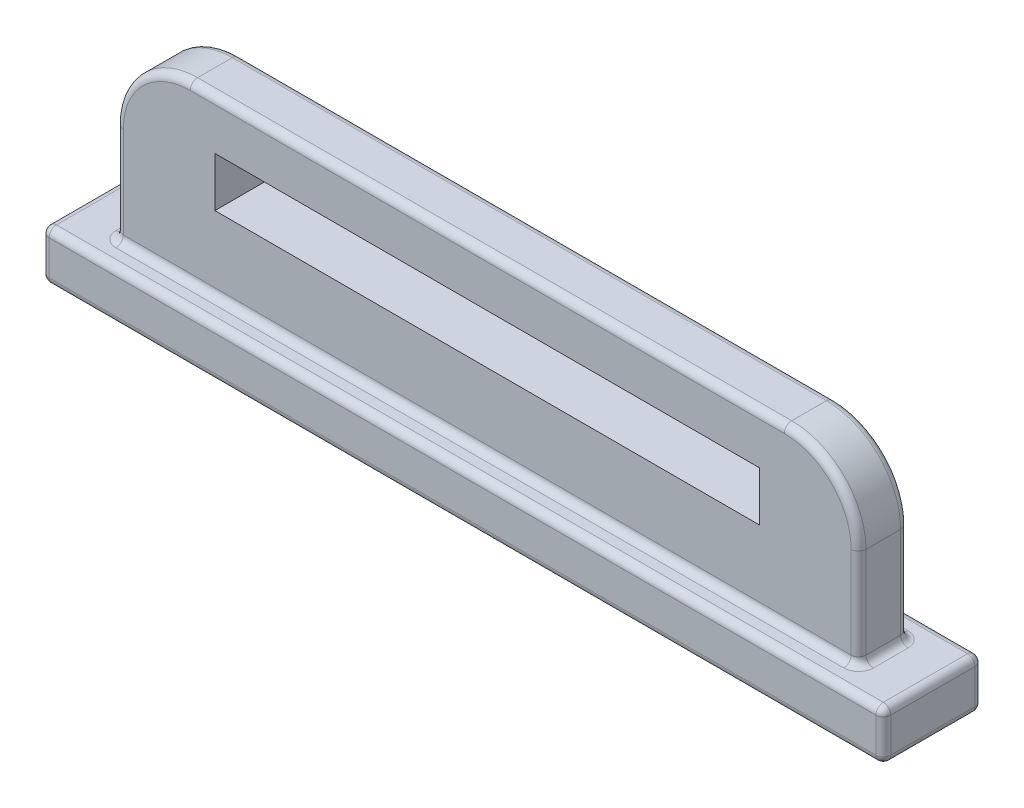
SolidWorks part; units mm, degrees
material "Plain Carbon Steel"
ref_plane "Front Plane" through (0, 0, 0) normal (0, 0, 1) x (1, 0, 0)
ref_plane "Top Plane" through (0, 0, 0) normal (0, 1, 0) x (1, 0, 0)
ref_plane "Right Plane" through (0, 0, 0) normal (1, 0, 0) x (0, 0, -1)
sketch "Sketch1" plane through (0, 0, 0) normal (0, 0, 1) x (1, 0, 0)
  line L0 (-110, 15) -> (-110, -5)
  line L1 (-150, -35) -> (150, -35)
  line L2 (-150, -35) -> (-150, 5)
  line L3 (-120, 35) -> (120, 35)
  line L4 (150, -35) -> (150, 5)
  line L5 (-150, -35) -> (150, 35) construction
  line L6 (-150, 35) -> (150, -35) construction
  line L7 (-110, 15) -> (110, 15)
  line L11 (-110, -5) -> (110, -5)
  line L12 (110, -5) -> (110, 15)
  arc A0 (120, 35) -> (150, 5) centre (120, 5) cw
  arc A1 (-150, 5) -> (-120, 35) centre (-120, 5) cw
  point P0 (0, 0)
  point P6 (0, 7.0518)
  dimension "D6" = 30
  dimension "D1" = 300
  dimension "D2" = 220
  dimension "D3" = 20
  dimension "D4" = 70
  dimension "D5" = 20
extrude "Boss-Extrude1" add sketch "Sketch1" along normal mid plane 20
sketch "Sketch2" plane through (0, -35, 0) normal (0, -1, 0) x (1, 0, 0)
  line L0 (-150, 10) -> (-150, -10) construction
  line L1 (-170, 20) -> (170, 20)
  line L2 (-170, 20) -> (-170, -20)
  line L3 (-170, -20) -> (170, -20)
  line L4 (170, 20) -> (170, -20)
  line L5 (-170, 20) -> (170, -20) construction
  line L6 (-170, -20) -> (170, 20) construction
  point P0 (0, 0)
  dimension "D1" = 340
  dimension "D2" = 40
  dimension "D3" = 20
extrude "Boss-Extrude2" add sketch "Sketch2" along normal blind 20
ref_plane "Plane1" through (0, -40, 0) normal (0, 1, 0) x (1, 0, 0)
sketch "Sketch3" plane through (0, -40, 0) normal (0, 1, 0) x (1, 0, 0)
  line L0 (0, 20) -> (0, -20)
  line L1 (-170, 20) -> (170, 20) construction
  line L2 (170, -20) -> (-170, -20) construction
fillet "Fillet1" radius 3 26 edges at (150, -15, 10) (141.2132, 26.2132, 10) (0, 35, 10) (-150, -15, 10) (150, -15, -10) (141.2132, 26.2132, -10) (0, 35, -10) (-150, -15, -10) (0, -35, 10) (150, -35, 0) (0, -35, -10) (-150, -35, 0) (0, -35, -20) (-170, -45, -20) (-170, -35, 0) (-170, -45, 20) (0, -35, 20) (170, -45, -20) (170, -45, 20) (170, -35, 0) (0, -55, -20) (-170, -55, 0) (0, -55, 20) (170, -55, 0) (-141.2132, 26.2132, 10) (-141.2132, 26.2132, -10)
